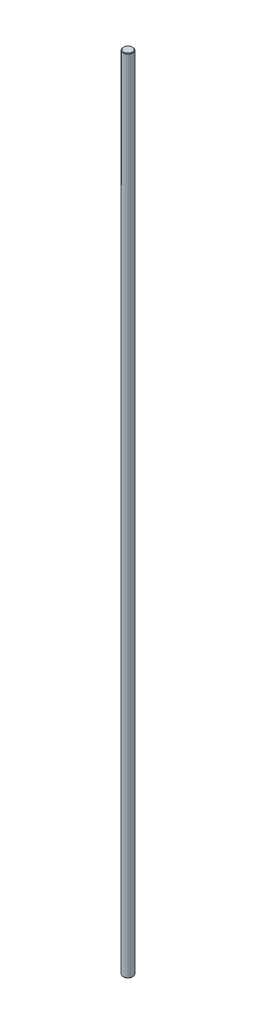
SolidWorks part; units mm, degrees
material "Chromowa stal nierdzewna"
ref_plane "Płaszczyzna przednia" through (0, 0, 0) normal (0, 0, 1) x (1, 0, 0)
ref_plane "Płaszczyzna górna" through (0, 0, 0) normal (0, 1, 0) x (1, 0, 0)
ref_plane "Płaszczyzna prawa" through (0, 0, 0) normal (1, 0, 0) x (0, 0, -1)
sketch "Szkic1" plane through (0, 0, 0) normal (0, 1, 0) x (1, 0, 0)
  circle A0 centre (0, 0) radius 2.5
  dimension "D1" = 5
extrude "Dodanie-wyciągnięcie1" add sketch "Szkic1" along normal blind 411
chamfer "Sfazowanie1" distance 0.25 angle 45 2 edges at (0, 0, 2.5) (0, 411, 2.5)
